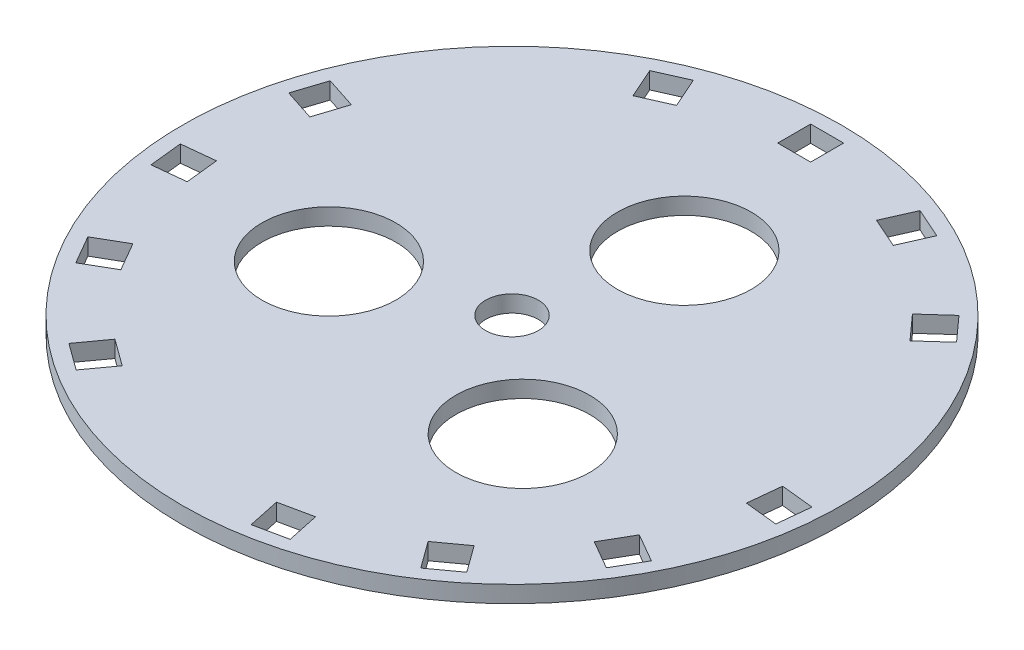
SolidWorks part; units mm, degrees
material "Delrin 2700 NC010, Low Viscosity Acetal Copolymer (SS)"
ref_plane "Front Plane" through (0, 0, 0) normal (0, 0, 1) x (1, 0, 0)
ref_plane "Top Plane" through (0, 0, 0) normal (0, 1, 0) x (1, 0, 0)
ref_plane "Right Plane" through (0, 0, 0) normal (1, 0, 0) x (0, 0, -1)
sketch "Sketch1" plane through (0, 0, 0) normal (0, 1, 0) x (1, 0, 0)
  line L0 (11.4604, 53.9171) -> (-52.4238, -17.0335) construction
  line L1 (-52.4238, -17.0335) -> (40.9634, -36.8836) construction
  line L2 (40.9634, -36.8836) -> (11.4604, 53.9171) construction
  line L3 (0, 0) -> (11.4604, 53.9171) construction
  line L4 (0, 0) -> (-52.4238, -17.0335) construction
  line L5 (0, 0) -> (40.9634, -36.8836) construction
  line L6 (0, 0) -> (25.989, 122.2685) construction
  line L7 (42.9831, 111.7866) -> (37.8989, 100.3673)
  line L8 (-6.2012, 119.4778) -> (6.2988, 119.4778)
  line L9 (-6.2012, 119.4778) -> (-6.2012, 106.9778)
  line L10 (-6.2012, 106.9778) -> (6.2988, 106.9778)
  line L11 (6.2988, 119.4778) -> (6.2988, 106.9778)
  line L12 (42.9831, 111.7866) -> (54.4024, 106.7024)
  line L13 (54.4024, 106.7024) -> (49.3182, 95.283)
  line L14 (37.8989, 100.3673) -> (49.3182, 95.283)
  line L15 (84.7869, 84.7552) -> (75.4976, 76.3911)
  line L16 (84.7869, 84.7552) -> (93.1511, 75.4659)
  line L17 (93.1511, 75.4659) -> (83.8617, 67.1018)
  line L18 (75.4976, 76.3911) -> (83.8617, 67.1018)
  line L23 (119.866, -6.0961) -> (107.4345, -4.7895)
  line L24 (119.866, -6.0961) -> (118.5594, -18.5276)
  line L25 (118.5594, -18.5276) -> (106.1279, -17.221)
  line L26 (107.4345, -4.7895) -> (106.1279, -17.221)
  line L27 (107.0757, -54.2071) -> (96.2504, -47.9571)
  line L28 (107.0757, -54.2071) -> (100.8257, -65.0324)
  line L29 (100.8257, -65.0324) -> (90.0004, -58.7824)
  line L30 (96.2504, -47.9571) -> (90.0004, -58.7824)
  line L31 (75.8228, -92.9563) -> (68.4755, -82.8436)
  line L32 (75.8228, -92.9563) -> (65.7101, -100.3036)
  line L33 (65.7101, -100.3036) -> (58.3628, -90.1909)
  line L34 (68.4755, -82.8436) -> (58.3628, -90.1909)
  line L35 (31.511, -115.6438) -> (28.9121, -103.417)
  line L36 (31.511, -115.6438) -> (19.2842, -118.2427)
  line L37 (19.2842, -118.2427) -> (16.6853, -106.0159)
  line L38 (28.9121, -103.417) -> (16.6853, -106.0159)
  line L43 (-64.7081, -100.5975) -> (-57.3607, -90.4848)
  line L44 (-64.7081, -100.5975) -> (-74.8208, -93.2502)
  line L45 (-74.8208, -93.2502) -> (-67.4735, -83.1375)
  line L46 (-57.3607, -90.4848) -> (-67.4735, -83.1375)
  line L47 (-99.9782, -65.4654) -> (-89.1529, -59.2154)
  line L48 (-99.9782, -65.4654) -> (-106.2282, -54.6401)
  line L49 (-106.2282, -54.6401) -> (-95.4029, -48.3901)
  line L50 (-89.1529, -59.2154) -> (-95.4029, -48.3901)
  line L51 (-117.9096, -19.0249) -> (-105.4781, -17.7183)
  line L52 (-117.9096, -19.0249) -> (-119.2162, -6.5934)
  line L53 (-119.2162, -6.5934) -> (-106.7847, -5.2868)
  line L54 (-105.4781, -17.7183) -> (-106.7847, -5.2868)
  line L55 (-115.4017, 30.694) -> (-103.5135, 26.8313)
  line L56 (-115.4017, 30.694) -> (-111.539, 42.5822)
  line L57 (-111.539, 42.5822) -> (-99.6508, 38.7195)
  line L58 (-103.5135, 26.8313) -> (-99.6508, 38.7195)
  line L63 (-54.2617, 106.499) -> (-49.1775, 95.0797)
  line L64 (-54.2617, 106.499) -> (-42.8424, 111.5832)
  line L65 (-42.8424, 111.5832) -> (-37.7582, 100.1639)
  line L66 (-49.1775, 95.0797) -> (-37.7582, 100.1639)
  line L67 (25.989, 122.2685) -> (6.2988, 106.9778) construction
  line L68 (25.989, 122.2685) -> (37.8989, 100.3673) construction
  line L70 (-92.8881, 75.0943) -> (-83.5988, 66.7302) [skipped]
  line L71 (-83.5988, 66.7302) -> (-75.2347, 76.0195) [skipped]
  line L72 (-84.524, 84.3837) -> (-75.2347, 76.0195) [skipped]
  line L73 (-92.8881, 75.0943) -> (-84.524, 84.3837) [skipped]
  line L74 (-18.1976, -118.3467) -> (-15.5987, -106.1198) [skipped]
  line L75 (-15.5987, -106.1198) -> (-27.8256, -103.5209) [skipped]
  line L76 (-30.4245, -115.7478) -> (-27.8256, -103.5209) [skipped]
  line L77 (-18.1976, -118.3467) -> (-30.4245, -115.7478) [skipped]
  line L78 (111.982, 43.0577) -> (100.0938, 39.195) [skipped]
  line L79 (100.0938, 39.195) -> (103.9565, 27.3068) [skipped]
  line L80 (115.8447, 31.1695) -> (103.9565, 27.3068) [skipped]
  line L81 (111.982, 43.0577) -> (115.8447, 31.1695) [skipped]
  circle A0 centre (0, 0) radius 125
  circle A1 centre (11.4604, 53.9171) radius 25.4
  circle A2 centre (40.9634, -36.8836) radius 25.4
  circle A3 centre (-52.4238, -17.0335) radius 25.4
  circle A4 centre (0, 0) radius 10
  point P74 (0.2988, -0.0649)
  dimension "D1" = 250
  dimension "D2" = 50.8
  dimension "D6" = 20
  dimension "D3" = 12.5
  dimension "D4" = 12.5
  dimension "D5" = 15
extrude "Boss-Extrude1" add sketch "Sketch1" along normal blind 6.35
